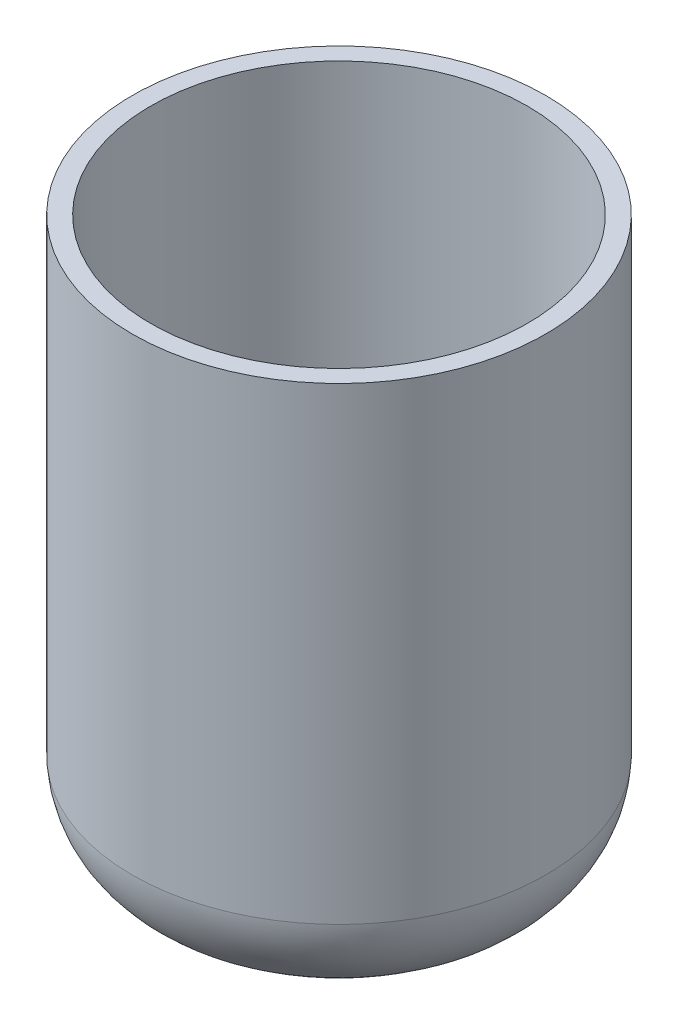
SolidWorks part; units mm, degrees
material "Q235"
ref_plane "前视基准面" through (0, 0, 0) normal (0, 0, 1) x (1, 0, 0)
ref_plane "上视基准面" through (0, 0, 0) normal (0, 1, 0) x (1, 0, 0)
ref_plane "右视基准面" through (0, 0, 0) normal (1, 0, 0) x (0, 0, -1)
sketch "草图1" plane through (0, 0, 0) normal (0, 0, 1) x (1, 0, 0)
  line L0 (225.25, 0) -> (225.25, -510.5149)
  line L1 (145, -610) -> (0, -610)
  line L2 (0, -610) -> (0, 0) construction
  arc A0 (145, -610) -> (225.25, -510.5149) centre (115.4404, -504.0461) ccw
  dimension "D4" = 110
  dimension "D1" = 225.25
  dimension "D2" = 610
  dimension "D3" = 145
revolve "旋转-薄壁1" add sketch "草图1" angle 360 about L2
